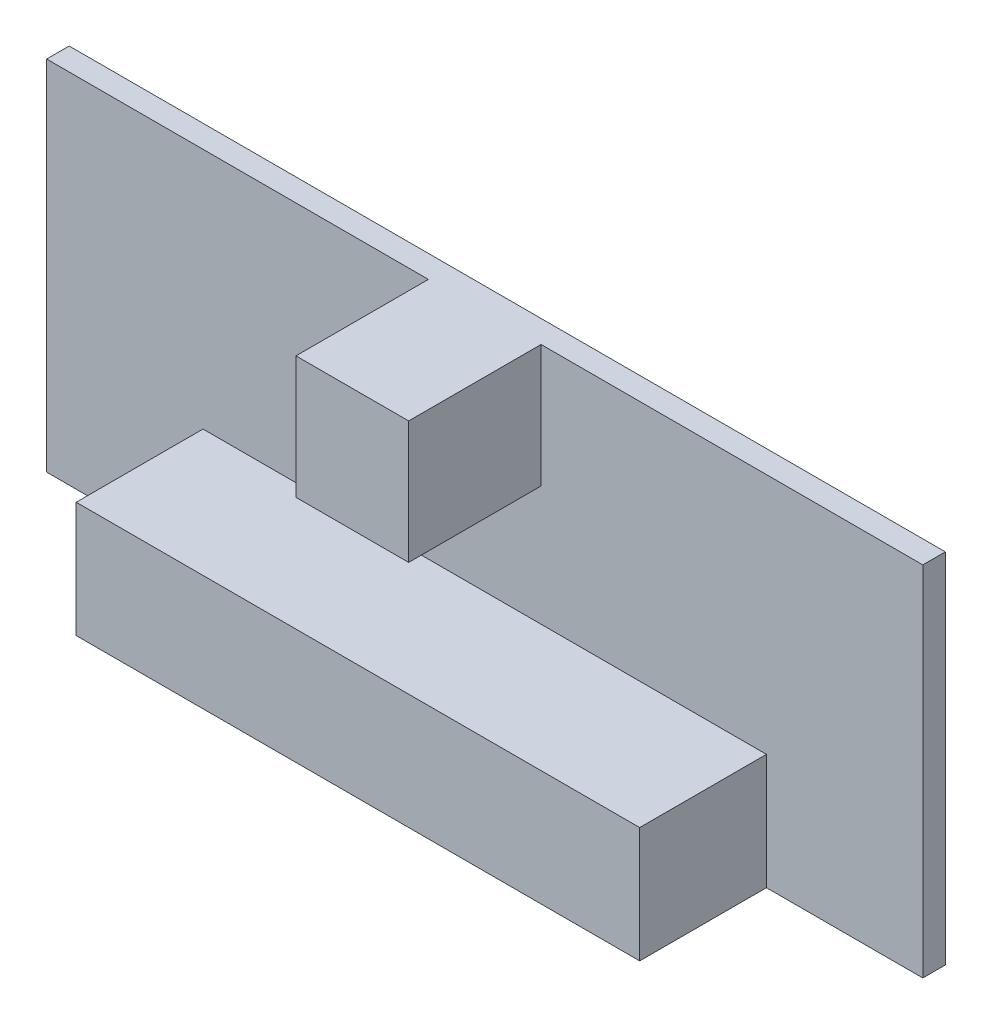
SolidWorks part; units mm, degrees
ref_plane "Front Plane" through (0, 0, 0) normal (0, 0, 1) x (1, 0, 0)
ref_plane "Top Plane" through (0, 0, 0) normal (0, 1, 0) x (1, 0, 0)
ref_plane "Right Plane" through (0, 0, 0) normal (1, 0, 0) x (0, 0, -1)
sketch "Sketch1" plane through (0, 0, 0) normal (0, 0, 1) x (1, 0, 0)
  line L0 (-31.1, -12.7) -> (31.1, -12.7)
  line L1 (31.1, -12.7) -> (31.1, 12.7)
  line L2 (31.1, 12.7) -> (-31.1, 12.7)
  line L3 (-31.1, 12.7) -> (-31.1, -12.7)
extrude "PCB" add sketch "Sketch1" along normal blind 1.6
ref_plane "P_Front_1p6" through (0, 0, 1.6) normal (0, 0, 1) x (1, 0, 0)
sketch "Sketch2" plane through (0, 0, 1.6) normal (0, 0, 1) x (1, 0, 0)
  line L0 (-20, -12.7) -> (20, -12.7)
  line L1 (20, -12.7) -> (20, -4.5)
  line L2 (20, -4.5) -> (-20, -4.5)
  line L3 (-20, -4.5) -> (-20, -12.7)
extrude "Servo_headers" add sketch "Sketch2" along normal blind 9
sketch "Sketch3" plane through (0, 0, 1.6) normal (0, 0, 1) x (1, 0, 0)
  line L0 (-4, 4) -> (4, 4)
  line L1 (4, 4) -> (4, 12.7)
  line L2 (4, 12.7) -> (-4, 12.7)
  line L3 (-4, 12.7) -> (-4, 4)
extrude "V+_terminal" add sketch "Sketch3" along normal blind 9.4
